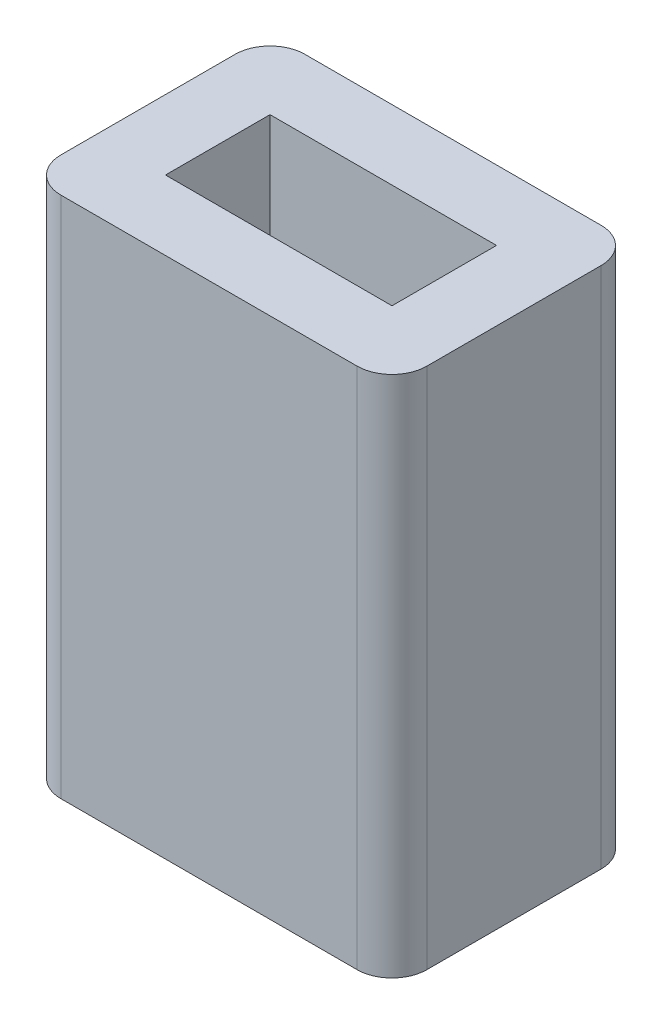
SolidWorks part; units mm, degrees
ref_plane "Front Plane" through (0, 0, 0) normal (0, 0, 1) x (1, 0, 0)
ref_plane "Top Plane" through (0, 0, 0) normal (0, 1, 0) x (1, 0, 0)
ref_plane "Right Plane" through (0, 0, 0) normal (1, 0, 0) x (0, 0, -1)
sketch "Sketch2" plane through (0, 0, 0) normal (0, 1, 0) x (1, 0, 0)
  line L0 (-5.25, -3.5) -> (-5.25, 3.5)
  line L1 (-3.25, -1.5) -> (3.25, -1.5)
  line L2 (-3.25, -1.5) -> (-3.25, 1.5)
  line L3 (-3.25, 1.5) -> (3.25, 1.5)
  line L4 (3.25, -1.5) -> (3.25, 1.5)
  line L5 (-3.25, -1.5) -> (3.25, 1.5) construction
  line L6 (-3.25, 1.5) -> (3.25, -1.5) construction
  line L7 (-5.25, 3.5) -> (5.25, 3.5)
  line L8 (5.25, -3.5) -> (5.25, 3.5)
  line L9 (-5.25, -3.5) -> (5.25, -3.5)
  point P0 (0, 0)
  dimension "D1" = 6.5
  dimension "D2" = 3
  dimension "D3" = 2
extrude "Boss-Extrude1" add sketch "Sketch2" along normal blind 15
fillet "Fillet1" radius 1 4 edges at (-5.25, 7.5, -3.5) (5.25, 7.5, -3.5) (5.25, 7.5, 3.5) (-5.25, 7.5, 3.5)
